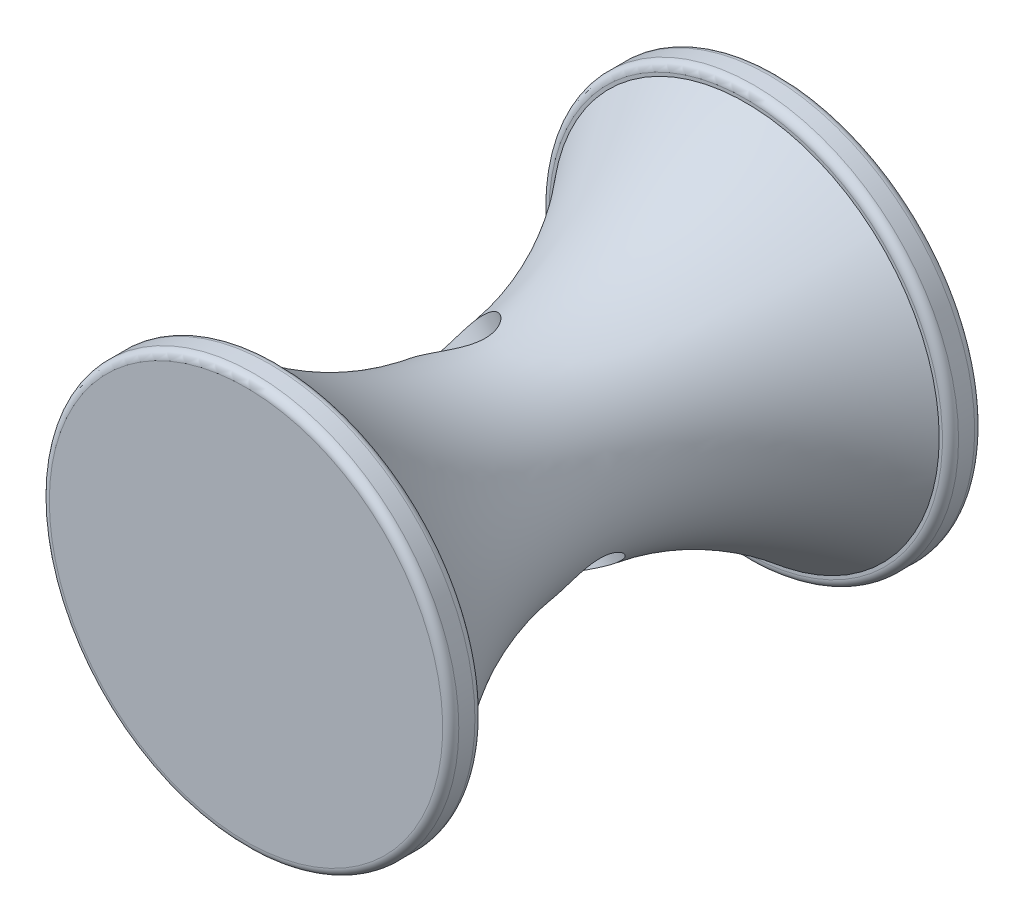
SolidWorks part; units mm, degrees
ref_plane "Front Plane" through (0, 0, 0) normal (0, 0, 1) x (1, 0, 0)
ref_plane "Top Plane" through (0, 0, 0) normal (0, 1, 0) x (1, 0, 0)
ref_plane "Right Plane" through (0, 0, 0) normal (1, 0, 0) x (0, 0, -1)
sketch "Sketch1" plane through (0, 0, 0) normal (0, 0, 1) x (1, 0, 0)
  circle A0 centre (0, 0) radius 2
  dimension "D1" = 4
sketch "Sketch10" plane through (0, 0, 0) normal (0, 1, 0) x (1, 0, 0)
  line L0 (0, 50) -> (0, -50) construction
  point P4 (0, 0)
  dimension "D1" = 100
ref_plane "Plane1" through (0, 0, 0) normal (-0.6516, 0.7586, 0) x (0, 0, 1)
sketch "Sketch3" plane through (0, 0, 0) normal (-0.6516, 0.7586, 0) x (0, 0, 1)
  line L0 (0, 0) -> (29, 0)
  line L1 (29, 0) -> (29, 12)
  line L2 (0, 0) -> (0, 12)
  line L3 (14.5, 0) -> (14.5, 6) construction
  line L5 (0, 0) -> (-2, 0)
  line L6 (0, 0) -> (0, 12.7)
  line L7 (0, 12.7) -> (-2, 12.7)
  line L8 (-2, 0) -> (-2, 12.7)
  line L9 (29, 0) -> (31, 0)
  line L10 (29, 0) -> (29, 12.7)
  line L11 (29, 12.7) -> (31, 12.7)
  line L12 (31, 0) -> (31, 12.7)
  spline S0 degree 2 poles (0, 12) (14.5, 0) (29, 12) knots 0 0 0 1 1 1
  dimension "D1" = 12
  dimension "D2" = 29
  dimension "D3" = 6
  dimension "D4" = 12.7
  dimension "D5" = 2
revolve "Revolve1" add sketch "Sketch3" angle 360 about L0
extrude "Cut-Extrude2" cut sketch "Sketch1" against normal blind 14 and the other way blind 2
fillet "Fillet1" radius 0.5 4 edges at (-12.7, 0, 29) (-12.7, 0, 0) (-12.7, 0, 31) (-12.7, 0, -2)
sketch "Sketch5" plane through (0, 0, 0) normal (-0.6516, 0.7586, 0) x (0, 0, 1)
  line L0 (-2, -12.7) -> (31, -12.7) construction
  line L1 (-2, 12.2) -> (-2, -12.2) construction
  line L2 (31, -12.2) -> (31, 12.2) construction
  line L3 (14.5, -12.7) -> (14.5, 12.7) construction
  line L4 (29.5, -12.7) -> (30.5, -12.7) construction
  line L5 (-2, 12.7) -> (31, 12.7) construction
  line L6 (-0.5, 12.7) -> (-1.5, 12.7) construction
  circle A0 centre (14.5, 0) radius 2.5
  point P19 (14.5, 0)
  dimension "D1" = 5
extrude "Cut-Extrude4" cut sketch "Sketch5" against normal up to surface and the other way up to surface up to face at (-12, 0, 29) other way up to face at (-12, 0, 29)
sketch "Sketch6" plane through (0, 0, -2) normal (0, 0, -1) x (-1, 0, 0)
  circle A0 centre (0, 0) radius 5
  circle A2 centre (0, 0) radius 2 construction
  dimension "D1" = 3
extrude "Boss-Extrude1" add sketch "Sketch6" along normal blind 5
sketch "Sketch8" plane through (0, 0, -7) normal (0, 0, -1) x (-1, 0, 0)
  circle A0 centre (0, 0) radius 2
  dimension "D1" = 4
extrude "Cut-Extrude5" cut sketch "Sketch8" against normal up to surface (5 mm away) up to face at (-5, 0, -2)
fillet "Fillet2" radius 0.5 3 edges at (-2, 0, -7) (-5, 0, -7) (-5, 0, -2)
sketch "Sketch9" plane through (0, 0, 0) normal (-0.6516, 0.7586, 0) x (0, 0, 1)
  line L0 (-7, 0) -> (-2, 0) construction
  line L1 (-7, 2.5) -> (-7, -2.5) construction
  line L2 (-2, 5.5) -> (-2, -5.5) construction
  circle A0 centre (-4.5, 0) radius 0.8
  dimension "D1" = 1.6
extrude "Cut-Extrude6" cut sketch "Sketch9" along normal up to next
